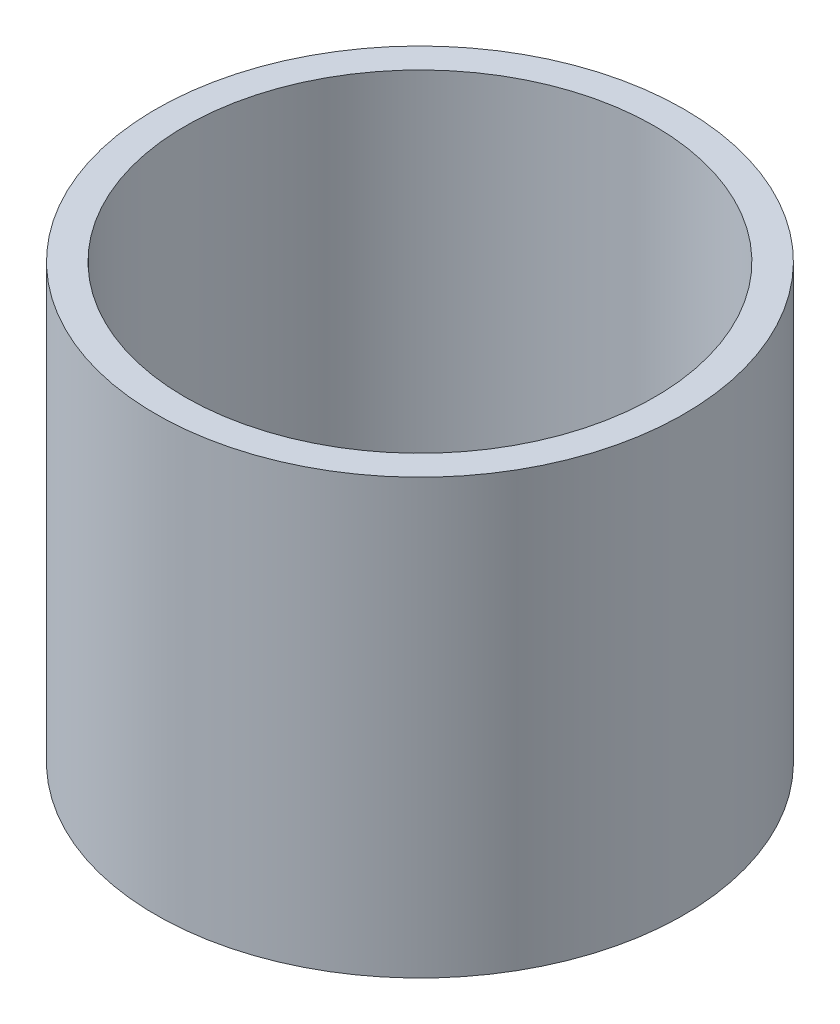
SolidWorks part; units mm, degrees
material "6061-T6 (SS)"
ref_plane "Front Plane" through (0, 0, 0) normal (0, 0, 1) x (1, 0, 0)
ref_plane "Top Plane" through (0, 0, 0) normal (0, 1, 0) x (1, 0, 0)
ref_plane "Right Plane" through (0, 0, 0) normal (1, 0, 0) x (0, 0, -1)
sketch "Sketch1" plane through (0, 0, 0) normal (1, 0, 0) x (0, 0, -1)
  line L0 (0, 0) -> (0, 23.9672) construction
  line L2 (12.7, 0) -> (14.2875, 0)
  line L3 (12.7, 0) -> (12.7, 23.465)
  line L4 (12.7, 23.465) -> (14.2875, 23.465)
  line L5 (14.2875, 0) -> (14.2875, 23.465)
  dimension "D1" = 25.4
  dimension "D2" = 28.575
  dimension "D3" = 23.465
revolve "Revolve1" add sketch "Sketch1" angle 360 about L0
